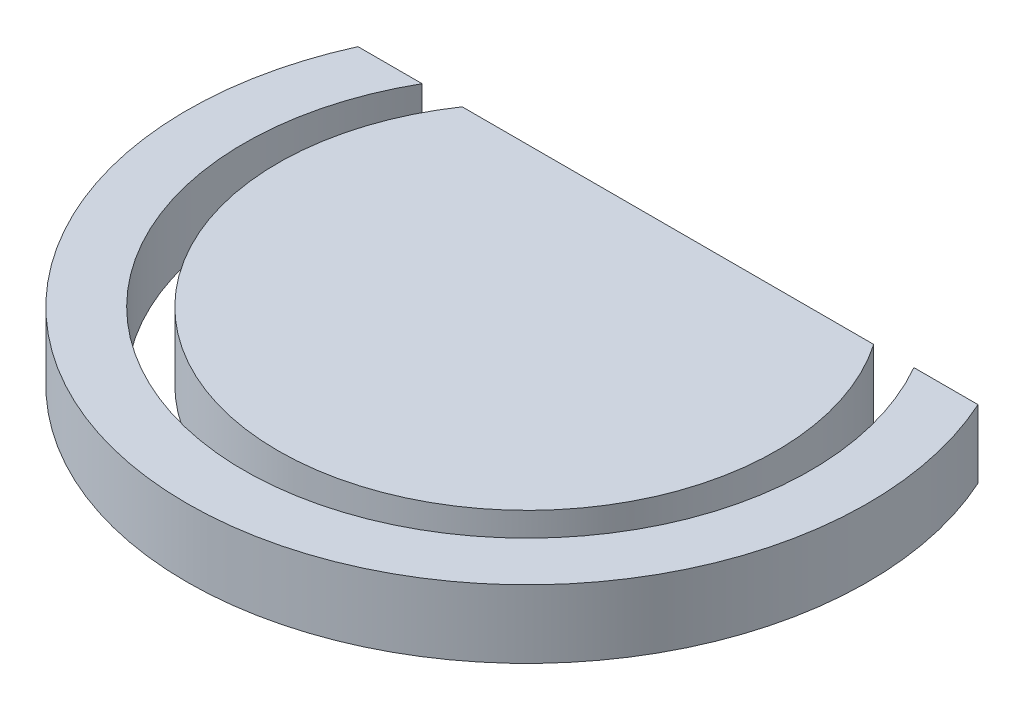
SolidWorks part; units mm, degrees
ref_plane "Ebene vorne" through (0, 0, 0) normal (0, 0, 1) x (1, 0, 0)
ref_plane "Ebene oben" through (0, 0, 0) normal (0, 1, 0) x (1, 0, 0)
ref_plane "Ebene rechts" through (0, 0, 0) normal (1, 0, 0) x (0, 0, -1)
sketch "Skizze1" plane through (0, 0, 0) normal (0, 1, 0) x (1, 0, 0)
  line L0 (45.5299, 20.6646) -> (-45.5299, 20.6646)
  arc A0 (-45.5299, 20.6646) -> (45.5299, 20.6646) centre (0, 0) ccw
  arc A1 (17.1231, 35.1601) -> (26.5765, 28.6901) centre (0, 0) ccw construction
  arc A6 (18.2177, 37.4077) -> (28.2755, 30.5241) centre (0, 0) ccw
  arc A7 (16.0285, 32.9125) -> (24.8776, 26.8561) centre (0, 0) ccw
  arc A8 (16.0285, 32.9125) -> (18.2177, 37.4077) centre (17.1231, 35.1601) ccw
  arc A9 (28.2755, 30.5241) -> (24.8776, 26.8561) centre (26.5765, 28.6901) ccw
  point P6 (-22.088, -32.2731)
  dimension "D1" = 100
  dimension "D2" = 5
extrude "Aufsatz-Linear austragen1" add sketch "Skizze1" along normal blind 10 contours L0 A7 | A6 L0 A0
